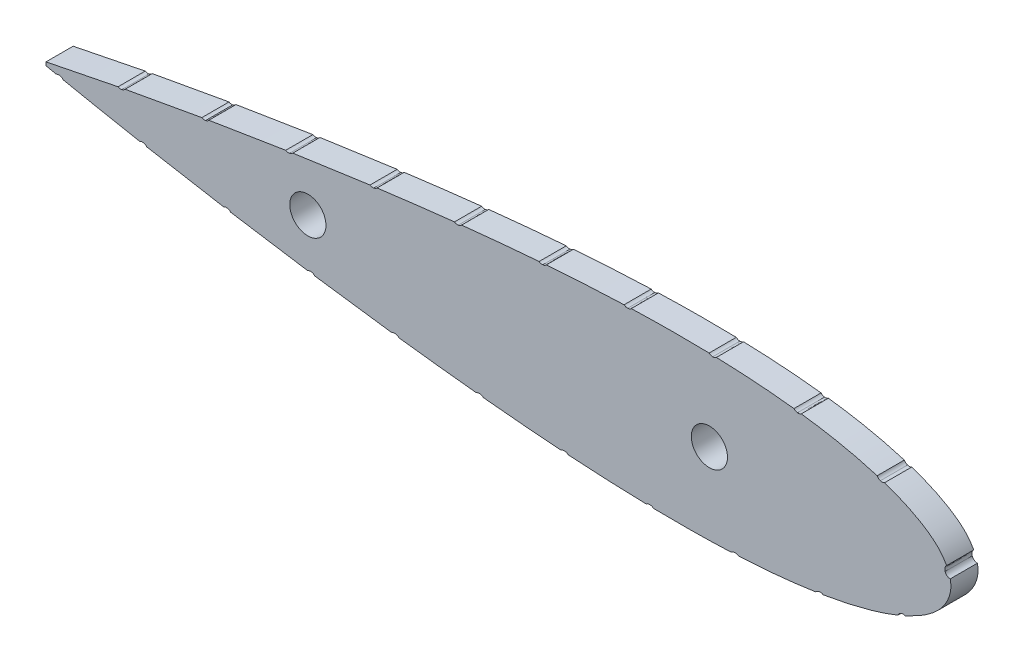
SolidWorks part; units mm, degrees
ref_plane "Front" through (0, 0, 0) normal (0, 0, 1) x (1, 0, 0)
ref_plane "Top" through (0, 0, 0) normal (0, 1, 0) x (1, 0, 0)
ref_plane "Right" through (0, 0, 0) normal (1, 0, 0) x (0, 0, -1)
sketch "Sketch1" plane through (0, 0, 0) normal (0, 0, 1) x (1, 0, 0)
  line L0 (-220, -0.189) -> (-220, 0.189)
  line L1 (-220, 0) -> (0, 0) construction
  circle A0 centre (-191.0623, 0) radius 2
  circle A1 centre (-146.6876, 0) radius 2
  spline S0 degree 3 poles (-1114.9727, 2853.0854) (-416.0108, -89.2098) (-318.8476, -18.6748) (-208.3441, 2.4978) (-200.0163, 3.9657) (-190.015, 5.5282) (-180.0152, 6.8843) (-170.0154, 7.9934) (-160.0131, 8.7795) (-151.668, 9.0587) (-144.996, 8.9473) (-139.9879, 8.6507) (-134.9704, 8.0782) (-130.7943, 7.2781) (-127.4635, 6.3265) (-124.92, 5.3651) (-122.7895, 4.2074) (-120.8297, 2.6061) (-119.4586, 0) (-120.8297, -2.6061) (-122.7895, -4.2074) (-124.92, -5.3651) (-127.4635, -6.3265) (-130.7943, -7.2781) (-134.9704, -8.0782) (-139.9879, -8.6507) (-144.996, -8.9473) (-151.668, -9.0587) (-160.0131, -8.7795) (-170.0154, -7.9934) (-180.0152, -6.8843) (-190.015, -5.5282) (-200.0163, -3.9657) (-208.3441, -2.4978) (-318.8482, 18.6749) (-416.0118, 89.2105) (-1114.9837, -2853.1315) knots -1.529222 -1.529222 -1.529222 -1.529222 0.024604 0.049152 0.098109 0.146905 0.195555 0.244056 0.29241 0.340644 0.364754 0.388906 0.413178 0.437756 0.450305 0.46323 0.477068 0.485036 0.5 0.514964 0.522932 0.53677 0.549695 0.562244 0.586822 0.611094 0.635246 0.659356 0.70759 0.755944 0.804445 0.853095 0.901891 0.950848 0.975396 2.52923 2.52923 2.52923 2.52923 only from (-220, 0.189) to (-220, -0.189) construction
  spline S1 degree 3 poles (-220, 0.189) (-218.3341, 0.5334) (-215.0062, 1.2214) (-208.3441, 2.4978) (-200.0163, 3.9657) (-190.015, 5.5282) (-180.0152, 6.8843) (-170.0154, 7.9934) (-160.0131, 8.7795) (-151.668, 9.0587) (-144.996, 8.9473) (-139.9879, 8.6507) (-134.9704, 8.0782) (-130.7943, 7.2781) (-127.4635, 6.3265) (-124.92, 5.3651) (-122.7895, 4.2074) (-120.8297, 2.6061) (-119.4586, 0) (-120.8297, -2.6061) (-122.7895, -4.2074) (-124.92, -5.3651) (-127.4635, -6.3265) (-130.7943, -7.2781) (-134.9704, -8.0782) (-139.9879, -8.6507) (-144.996, -8.9473) (-151.668, -9.0587) (-160.0131, -8.7795) (-170.0154, -7.9934) (-180.0152, -6.8843) (-190.015, -5.5282) (-200.0163, -3.9657) (-208.3441, -2.4978) (-215.0062, -1.2214) (-218.3341, -0.5334) (-220, -0.189) knots 0 0 0 0 0.024604 0.049152 0.098109 0.146905 0.195555 0.244056 0.29241 0.340644 0.364754 0.388906 0.413178 0.437756 0.450305 0.46323 0.477068 0.485036 0.5 0.514964 0.522932 0.53677 0.549695 0.562244 0.586822 0.611094 0.635246 0.659356 0.70759 0.755944 0.804445 0.853095 0.901891 0.950848 0.975396 1 1 1 1
  dimension "D1" = 4
  dimension "D2" = 4
extrude "Boss-Extrude1" add sketch "Sketch1" along normal blind 3
sketch "Sketch2" plane through (0, 0, 3) normal (0, 0, 1) x (1, 0, 0)
  spline S0 degree 3 poles (-1114.9727, -2853.0854) (-416.0108, 89.2098) (-318.8476, 18.6748) (-208.3441, -2.4978) (-200.0163, -3.9657) (-190.015, -5.5282) (-180.0152, -6.8843) (-170.0154, -7.9934) (-160.0131, -8.7795) (-151.668, -9.0587) (-144.996, -8.9473) (-139.9879, -8.6507) (-134.9704, -8.0782) (-130.7943, -7.2781) (-127.4635, -6.3265) (-124.92, -5.3651) (-122.7895, -4.2074) (-120.8297, -2.6061) (-119.4586, 0) (-120.8297, 2.6061) (-122.7895, 4.2074) (-124.92, 5.3651) (-127.4635, 6.3265) (-130.7943, 7.2781) (-134.9704, 8.0782) (-139.9879, 8.6507) (-144.996, 8.9473) (-151.668, 9.0587) (-160.0131, 8.7795) (-170.0154, 7.9934) (-180.0152, 6.8843) (-190.015, 5.5282) (-200.0163, 3.9657) (-208.3441, 2.4978) (-318.8482, -18.6749) (-416.0118, -89.2105) (-1114.9837, 2853.1315) knots -1.529222 -1.529222 -1.529222 -1.529222 0.024604 0.049152 0.098109 0.146905 0.195555 0.244056 0.29241 0.340644 0.364754 0.388906 0.413178 0.437756 0.450305 0.46323 0.477068 0.485036 0.5 0.514964 0.522932 0.53677 0.549695 0.562244 0.586822 0.611094 0.635246 0.659356 0.70759 0.755944 0.804445 0.853095 0.901891 0.950848 0.975396 2.52923 2.52923 2.52923 2.52923 only from (-220, -0.189) to (-220, 0.189) construction
  spline S1 degree 3 poles (-220, -0.189) (-218.3341, -0.5334) (-215.0062, -1.2214) (-208.3441, -2.4978) (-200.0163, -3.9657) (-190.015, -5.5282) (-180.0152, -6.8843) (-170.0154, -7.9934) (-160.0131, -8.7795) (-151.668, -9.0587) (-144.996, -8.9473) (-139.9879, -8.6507) (-134.9704, -8.0782) (-130.7943, -7.2781) (-127.4635, -6.3265) (-124.92, -5.3651) (-122.7895, -4.2074) (-120.8297, -2.6061) (-119.4586, 0) (-120.8297, 2.6061) (-122.7895, 4.2074) (-124.92, 5.3651) (-127.4635, 6.3265) (-130.7943, 7.2781) (-134.9704, 8.0782) (-139.9879, 8.6507) (-144.996, 8.9473) (-151.668, 9.0587) (-160.0131, 8.7795) (-170.0154, 7.9934) (-180.0152, 6.8843) (-190.015, 5.5282) (-200.0163, 3.9657) (-208.3441, 2.4978) (-215.0062, 1.2214) (-218.3341, 0.5334) (-220, 0.189) knots 0 0 0 0 0.024604 0.049152 0.098109 0.146905 0.195555 0.244056 0.29241 0.340644 0.364754 0.388906 0.413178 0.437756 0.450305 0.46323 0.477068 0.485036 0.5 0.514964 0.522932 0.53677 0.549695 0.562244 0.586822 0.611094 0.635246 0.659356 0.70759 0.755944 0.804445 0.853095 0.901891 0.950848 0.975396 1 1 1 1 construction
  text T0 ". . . . . . . . . . . . . . . . . . . . . . ." font "Century Gothic" height in points 28
extrude "Cut-Extrude1" cut sketch "Sketch2" against normal blind 10
sketch "Sketch3" plane through (0, 0, 0) normal (0, 0, -1) x (-1, 0, 0)
  line L0 (220, 0.189) -> (220, -0.189) construction
  line L1 (114.29, 25) -> (224.29, 25)
  line L2 (114.29, 25) -> (114.29, -25)
  line L3 (114.29, -25) -> (224.29, -25)
  line L4 (224.29, 25) -> (224.29, -25)
  point P11 (0, 0)
  dimension "D1" = 4.29
  dimension "D2" = 50
  dimension "D3" = 110
